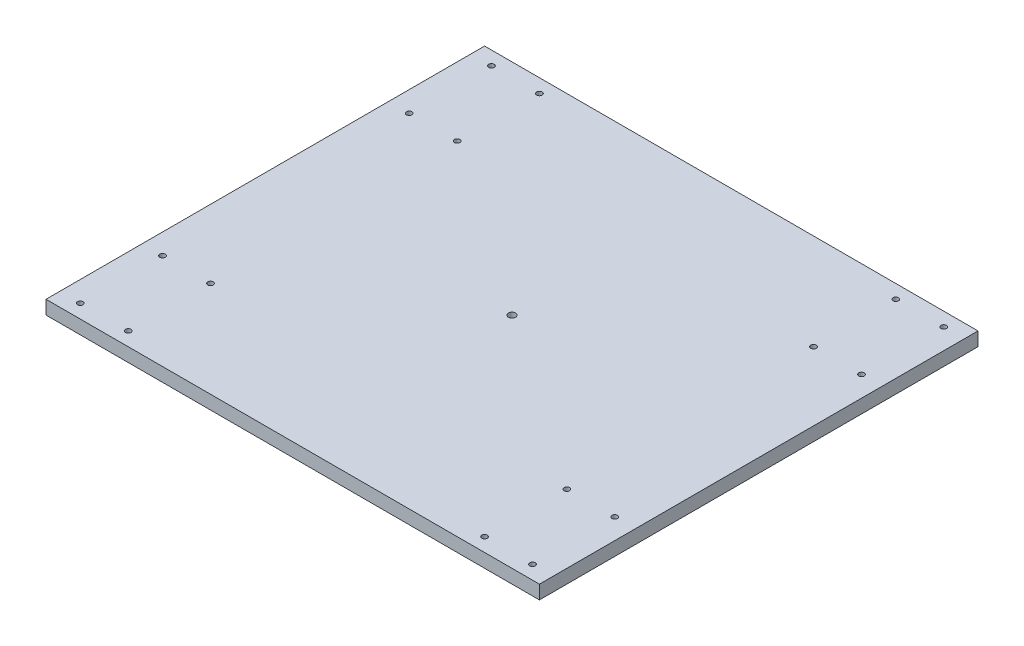
SolidWorks part; units mm, degrees
ref_plane "Front" through (0, 0, 0) normal (0, 0, 1) x (1, 0, 0)
ref_plane "Top" through (0, 0, 0) normal (0, 1, 0) x (1, 0, 0)
ref_plane "Right" through (0, 0, 0) normal (1, 0, 0) x (0, 0, -1)
sketch "Sketch1" plane through (0, 0, 0) normal (0, 1, 0) x (1, 0, 0)
  line L1 (-228.6, -203.2) -> (228.6, -203.2)
  line L2 (-228.6, -203.2) -> (-228.6, 203.2)
  line L3 (-228.6, 203.2) -> (228.6, 203.2)
  line L4 (228.6, -203.2) -> (228.6, 203.2)
  line L5 (-228.6, -203.2) -> (228.6, 203.2) construction
  line L6 (-228.6, 203.2) -> (228.6, -203.2) construction
  point P0 (0, 0)
  dimension "D1" = 457.2
  dimension "D2" = 406.4
extrude "Boss-Extrude1" add sketch "Sketch1" along normal blind 12.7 contours L3 L4 L1 L2
sketch "Sketch2" plane through (0, 12.7, 0) normal (0, 1, 0) x (1, 0, 0)
  line L0 (-228.6, -203.2) -> (228.6, -203.2) construction
  line L1 (-228.6, -203.2) -> (-228.6, 203.2) construction
  point P0 (-209.55, -190.5)
  point P1 (-209.55, -114.3)
  point P2 (-165.1, -114.3)
  point P3 (-165.1, -190.5)
  dimension "D1" = 44.45
  dimension "D2" = 76.2
  dimension "D3" = 12.7
  dimension "D4" = 19.05
hole_wizard "1/4-20 Tapped Hole1" positions "Sketch3" profile "Sketch4" tap size "1/4-20" standard "ANSI Inch"
sketch "Sketch3" plane through (0, 12.7, 0) normal (0, 1, 0) x (1, 0, 0)
  point P0 (-209.55, -190.5)
  point P3 (-209.55, -114.3)
  point P6 (-165.1, -114.3)
  point P9 (-165.1, -190.5)
sketch "Sketch4" plane through (-209.55, 12.7, 190.5) normal (1, 0, 0) x (0, 0, 1)
  line L0 (0, 0) -> (0, 18.0438)
  line L1 (0, 18.0438) -> (2.5527, 16.51)
  line L2 (2.5527, 16.51) -> (2.5527, 0)
  line L5 (2.5527, 0) -> (0, 0)
  line L10 (0, 18.0438) -> (-2.5527, 16.51) construction
  line L11 (0, -6.35) -> (0, 107.95) construction
  dimension "Tap Drill Dia." = 5.1054
  dimension "Tap Drill Depth" = 16.51
  dimension "Drill Angle" = 118
mirror "Mirror1" about plane through (0, 0, 0) normal (1, 0, 0) of "1/4-20 Tapped Hole1"
mirror "Mirror2" about plane through (0, 0, 0) normal (0, 0, 1) of "Mirror1", "1/4-20 Tapped Hole1"
sketch "Sketch5" plane through (0, 12.7, 0) normal (0, 1, 0) x (1, 0, 0)
  point P0 (0, 0)
hole_wizard "1/4 Clearance Hole1" positions "Sketch6" profile "Sketch8" hole size "1/4" standard "ANSI Inch" end condition up to next
sketch "Sketch6" plane through (0, 12.7, 0) normal (0, 1, 0) x (1, 0, 0)
  point P0 (0, 0)
sketch "Sketch8" plane through (0, 12.7, 0) normal (1, 0, 0) x (0, 0, 1)
  line L0 (0, 0) -> (0, 12.7)
  line L1 (0, 12.7) -> (3.3782, 12.7)
  line L2 (3.3782, 12.7) -> (3.3782, 0)
  line L5 (3.3782, 0) -> (0, 0)
  line L11 (0, -6.35) -> (0, 107.95) construction
  dimension "Thru Hole Dia." = 6.7564
  dimension "Thru Hole Depth" = 12.7
